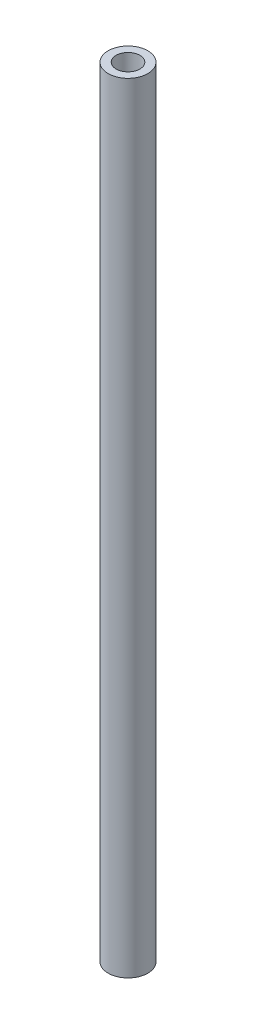
SolidWorks part; units mm, degrees
material "Thornel VCB-20 Carbon Cloth"
ref_plane "Front Plane" through (0, 0, 0) normal (0, 0, 1) x (1, 0, 0)
ref_plane "Top Plane" through (0, 0, 0) normal (0, 1, 0) x (1, 0, 0)
ref_plane "Right Plane" through (0, 0, 0) normal (1, 0, 0) x (0, 0, -1)
sketch "Sketch1" plane through (0, 0, 0) normal (0, 1, 0) x (1, 0, 0)
  circle A0 centre (0, 0) radius 1.5
  circle A1 centre (0, 0) radius 2.5
  dimension "D1" = 3
  dimension "D2" = 5
extrude "Boss-Extrude1" add sketch "Sketch1" along normal blind 98.298
